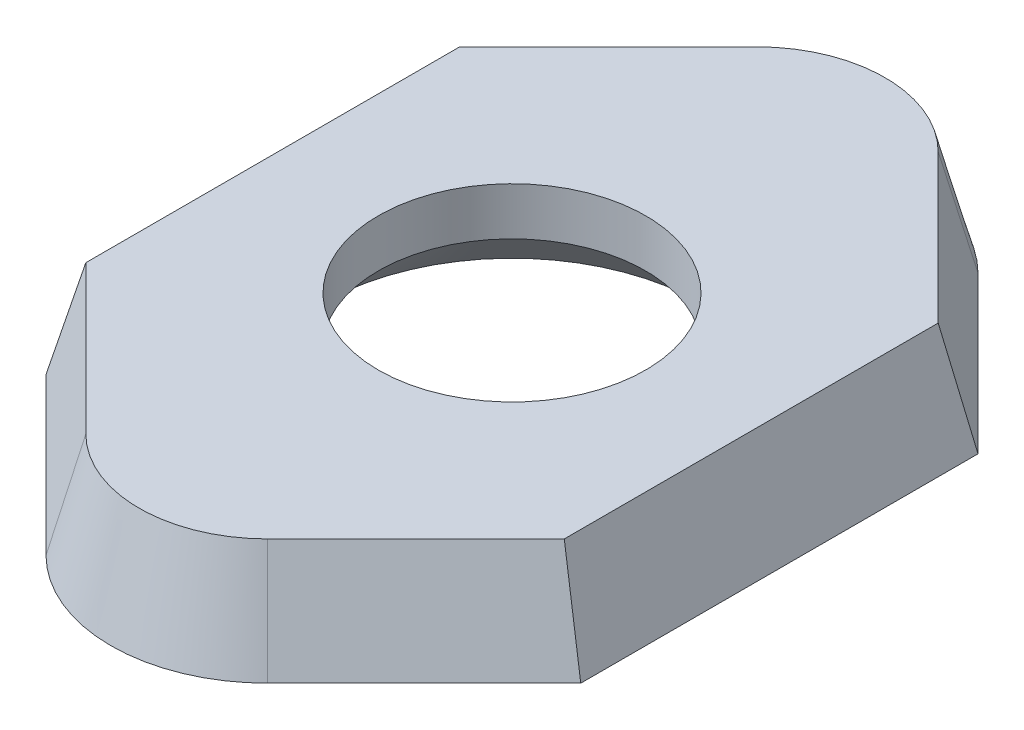
SolidWorks part; units mm, degrees
material "1060 Alloy"
ref_plane "Front" through (0, 0, 0) normal (0, 0, 1) x (1, 0, 0)
ref_plane "Top" through (0, 0, 0) normal (0, 1, 0) x (1, 0, 0)
ref_plane "Right" through (0, 0, 0) normal (1, 0, 0) x (0, 0, -1)
sketch "Sketch1" plane through (0, 0, 0) normal (0, 1, 0) x (1, 0, 0)
  line L0 (-29.5874, 0) -> (47.5733, 0) construction
  line L9 (0, -25.6508) -> (0, 32.7332) construction
  line L10 (-5.799, -18.601) -> (-14, -10.4)
  line L14 (14, 10.4) -> (5.799, 18.601)
  line L15 (5.799, 18.601) -> (-5.799, 18.601)
  line L16 (-5.799, 18.601) -> (-14, 10.4)
  line L19 (-14, 10.4) -> (-14, 4.601) [skipped]
  line L20 (-10.598, -4.6) -> (-9.8995, -5.2985) [skipped]
  line L21 (0, -9.399) -> (5.799, -9.399) [skipped]
  line L22 (12.3995, -2.7985) -> (13.098, -2.1) [skipped]
  line L23 (14, 9.601) -> (14, 15.4) [skipped]
  line L24 (5.799, -18.601) -> (-5.799, -18.601)
  line L25 (14, -10.4) -> (5.799, -18.601)
  line L26 (-14, 10.4) -> (-14, -10.4)
  line L27 (14, 10.4) -> (14, -10.4)
  circle A0 centre (0, 4.601) radius 14 construction
  dimension "D1" = 28
  dimension "D2" = 10.4
extrude "Boss-Extrude1" add sketch "Sketch1" along normal blind 5.5
draft "Draft1" type of draft neutral plane draft angle 15 faces to draft 8 face at (0, 2.75, 18.601) face at (-9.8995, 2.75, 14.5005) face at (-14, 2.75, 0) face at (9.8995, 2.75, 14.5005) face at (-9.8995, 2.75, -14.5005) face at (0, 2.75, -18.601) face at (9.8995, 2.75, -14.5005) face at (14, 2.75, 0) neutral plane through (0, 0, 0) neutral plane normal (0, -1, 0) reverse direction yes parameters "D1"=15
ref_plane "Plane1" through (14, 0, -10.4) normal (-0.7071, 0, -0.7071) x (-0.7071, 0, 0.7071)
sketch "Sketch7" plane through (14, 0, -10.4) normal (-0.7071, 0, -0.7071) x (-0.7071, 0, 0.7071)
  line L0 (-3.2636, 5.754) -> (1.3763, 5.754)
  line L1 (1.4989, 5.5941) -> (-0.1597, -0.596)
  line L2 (1.4737, 5.5) -> (0, 0) construction
  line L3 (1.4737, 5.5) -> (8.8114, 5.5) construction
  line L4 (-3.2636, 5.754) -> (-3.2636, -0.596)
  line L5 (-3.2636, -0.596) -> (-0.1597, -0.596)
  arc A0 (1.4989, 5.5941) -> (1.3763, 5.754) centre (1.3763, 5.627) ccw
  dimension "D1" = 0.127
  dimension "D2" = 4.7625
  dimension "D3" = 6.35
  dimension "D4" = 0.254
sketch "Sketch9" plane through (0, 0, 0) normal (0, -1, 0) x (1, 0, 0)
  line L0 (-5.799, -18.601) -> (-14, -10.4) construction
  line L1 (14, -10.4) -> (5.799, -18.601) construction
  line L2 (-5.799, -18.601) -> (-14, -10.4)
  line L3 (14, -10.4) -> (5.799, -18.601)
  line L4 (5.799, 18.601) -> (14, 10.4) construction
  line L5 (-14, 10.4) -> (-5.799, 18.601) construction
  line L6 (5.799, 18.601) -> (14, 10.4) construction
  line L7 (-14, 10.4) -> (-5.799, 18.601) construction
  line L8 (-14, -10.4) -> (-20.8079, -3.5921)
  line L9 (-14, 10.4) -> (-20.8079, 3.5921) construction
  line L10 (0, 24.3853) -> (0, -34.271) construction
  line L11 (14, -10.4) -> (20.8079, -3.5921)
  line L12 (14, 10.4) -> (20.8079, 3.5921) construction
  arc A0 (-5.799, -18.601) -> (5.799, -18.601) centre (0, -12.802) ccw
  arc A1 (-5.799, 18.601) -> (5.799, 18.601) centre (0, 12.802) cw construction
  arc A2 (-20.8079, 3.5921) -> (-20.8079, -3.5921) centre (-17.2158, 0) ccw construction
  arc A3 (20.8079, 3.5921) -> (20.8079, -3.5921) centre (17.2158, 0) cw construction
  dimension "D1" = 5.08
sketch "Sketch10" plane through (0, 0, 0) normal (0, -1, 0) x (1, 0, 0)
  line L0 (-14, -10.4) -> (14, -10.4)
  line L1 (14, -10.4) -> (5.799, -18.601) construction
  line L2 (-5.799, -18.601) -> (-14, -10.4) construction
  line L3 (14, -10.4) -> (5.799, -18.601)
  line L4 (-5.799, -18.601) -> (-14, -10.4)
  line L5 (-14, 10.4) -> (14, 10.4)
  line L6 (14, 10.4) -> (5.799, 18.601)
  line L7 (-14, 10.4) -> (-5.799, 18.601) construction
  line L8 (-14, 10.4) -> (-5.799, 18.601)
  arc A1 (-5.799, -18.601) -> (5.799, -18.601) centre (0, -12.802) ccw construction
  arc A2 (-5.799, -18.601) -> (5.799, -18.601) centre (0, -12.802) ccw
  arc A3 (5.799, 18.601) -> (-5.799, 18.601) centre (0, 12.802) ccw construction
  arc A4 (5.799, 18.601) -> (-5.799, 18.601) centre (0, 12.802) ccw
extrude "Boss-Extrude3" add sketch "Sketch10" against normal up to surface (5.5 mm away) up to face at (0, 5.5, 0)
sweep "Cut-Sweep1" cut profiles "Sketch7" path "Sketch9"
mirror "Mirror1" about plane through (0, 0, 0) normal (0, 0, 1) of "Cut-Sweep1"
sketch "Sketch11" plane through (0, 5.5, 0) normal (0, 1, 0) x (1, 0, 0)
  line L1 (-18, 22.5) -> (18, 22.5)
  line L2 (-18, 22.5) -> (-18, -22.5)
  line L3 (-18, -22.5) -> (18, -22.5)
  line L4 (18, 22.5) -> (18, -22.5)
  line L5 (-18, 22.5) -> (18, -22.5) construction
  line L6 (-18, -22.5) -> (18, 22.5) construction
  point P0 (0, 0)
  dimension "D1" = 36
  dimension "D2" = 45
extrude "Boss-Extrude4" add sketch "Sketch11" along normal blind 7
sketch "Sketch12" plane through (0, 5.5, 0) normal (0, -1, 0) x (1, 0, 0)
  line L0 (-18, -22.5) -> (-18, 22.5) construction
  line L1 (-18, 22.5) -> (18, 22.5) construction
  line L2 (0, 22.8662) -> (0, -23.1229) construction
  line L3 (-20.0887, 0) -> (22.2469, 0) construction
  circle A0 centre (-13, 17.5) radius 1.65
  circle A1 centre (13, 17.5) radius 1.65
  circle A2 centre (13, -17.5) radius 1.65
  circle A3 centre (-13, -17.5) radius 1.65
  dimension "D1" = 5
  dimension "D2" = 5
  dimension "D3" = 3.3
extrude "Cut-Extrude1" cut sketch "Sketch12" against normal blind 10
hole_wizard "CSK for M4 Flat Head Machine Screw1" positions "3DSketch1" profile "Sketch3" countersink size "M4" standard "ANSI Metric"
sketch3d "3DSketch1"
  line L2 (13, 12.5, -17.5) -> (13, 5.5, -17.5) construction
  line L3 (-13, 12.5, -17.5) -> (-13, 5.5, -17.5) construction
  line L4 (13, 12.5, 17.5) -> (13, 5.5, 17.5) construction
  line L5 (-13, 12.5, 17.5) -> (-13, 5.5, 17.5) construction
  point P10 (13, 5.5, -17.5)
  point P14 (-13, 5.5, -17.5)
  point P18 (13, 5.5, 17.5)
  point P22 (-13, 5.5, 17.5)
sketch "Sketch3" plane through (13, 5.5, -17.5) normal (1, 0, 0) x (0, 0, -1)
  line L0 (0, 0) -> (0, 4.3519)
  line L1 (0, 4.3519) -> (2.25, 3)
  line L2 (2.25, 3) -> (2.25, 2.45)
  line L3 (2.25, 2.45) -> (4.7, 0)
  line L5 (4.7, 0) -> (0, 0)
  line L6 (-2.25, 2.45) -> (-4.7, 0) construction
  line L10 (0, 4.3519) -> (-2.25, 3) construction
  line L11 (0, -6.35) -> (0, 107.95) construction
  dimension "Hole Dia." = 4.5
  dimension "Hole Depth" = 3
  dimension "Near C'Sink Dia." = 9.4
  dimension "Near C'Sink Angle" = 90
  dimension "Drill Angle" = 118
fillet "Fillet1" radius 5 4 edges at (18, 9, -22.5) (-18, 9, -22.5) (-18, 9, 22.5) (18, 9, 22.5)
sketch "Sketch13" plane through (0, 0, 0) normal (1, 0, 0) x (0, 0, -1)
  line L1 (0, 14.8) -> (0, -4.2)
  line L2 (-10.4, 0) -> (10.4, 0) construction
  line L3 (0, -5.1164) -> (0, 15.2723) construction
  line L7 (0, -4.2) -> (7, -4.2)
  line L8 (7, -4.2) -> (7, 2.8)
  line L9 (7, 2.8) -> (7, 21.4597)
  line L10 (7, 21.4597) -> (0, 21.4597)
  line L11 (0, 21.4597) -> (0, 14.8)
  dimension "D1" = 7
  dimension "D2" = 7
  dimension "D4" = 4.2
revolve "Cut-Revolve1" cut sketch "Sketch13" angle 360 about L3
chamfer "Chamfer1" distance 3 angle 45 1 edges at (0, 0, 7)
sketch "Sketch14" plane through (0, 12.5, 0) normal (0, 1, 0) x (1, 0, 0)
  line L4 (18, -17.5) -> (18, 17.5)
  line L5 (13, 22.5) -> (-13, 22.5)
  line L6 (-18, 17.5) -> (-18, -17.5)
  line L7 (-13, -22.5) -> (13, -22.5)
  line L8 (18, -17.5) -> (18, 17.5)
  line L9 (13, 22.5) -> (-13, 22.5)
  line L10 (-18, 17.5) -> (-18, -17.5)
  line L11 (-13, -22.5) -> (13, -22.5)
  arc A4 (18, 17.5) -> (13, 22.5) centre (13, 17.5) ccw
  arc A5 (-13, 22.5) -> (-18, 17.5) centre (-13, 17.5) ccw
  arc A6 (-18, -17.5) -> (-13, -22.5) centre (-13, -17.5) ccw
  arc A7 (13, -22.5) -> (18, -17.5) centre (13, -17.5) ccw
  arc A8 (18, 17.5) -> (13, 22.5) centre (13, 17.5) ccw
  arc A9 (-13, 22.5) -> (-18, 17.5) centre (-13, 17.5) ccw
  arc A10 (-18, -17.5) -> (-13, -22.5) centre (-13, -17.5) ccw
  arc A11 (13, -22.5) -> (18, -17.5) centre (13, -17.5) ccw
  dimension "D1" = 0
extrude "Cut-Extrude2" cut sketch "Sketch14" against normal up to surface (7 mm away)
sketch "Sketch15" plane through (0, 5.5, 0) normal (0, 1, 0) x (1, 0, 0)
  line L0 (0, 19.5293) -> (0, -19.5293)
  circle A0 centre (0, 0) radius 7 construction
  circle A1 centre (0, 0) radius 7
  arc A2 (4.7569, 17.5589) -> (-4.7569, 17.5589) centre (0, 12.802) ccw construction
  arc A3 (-4.7569, -17.5589) -> (4.7569, -17.5589) centre (0, -12.802) ccw construction
